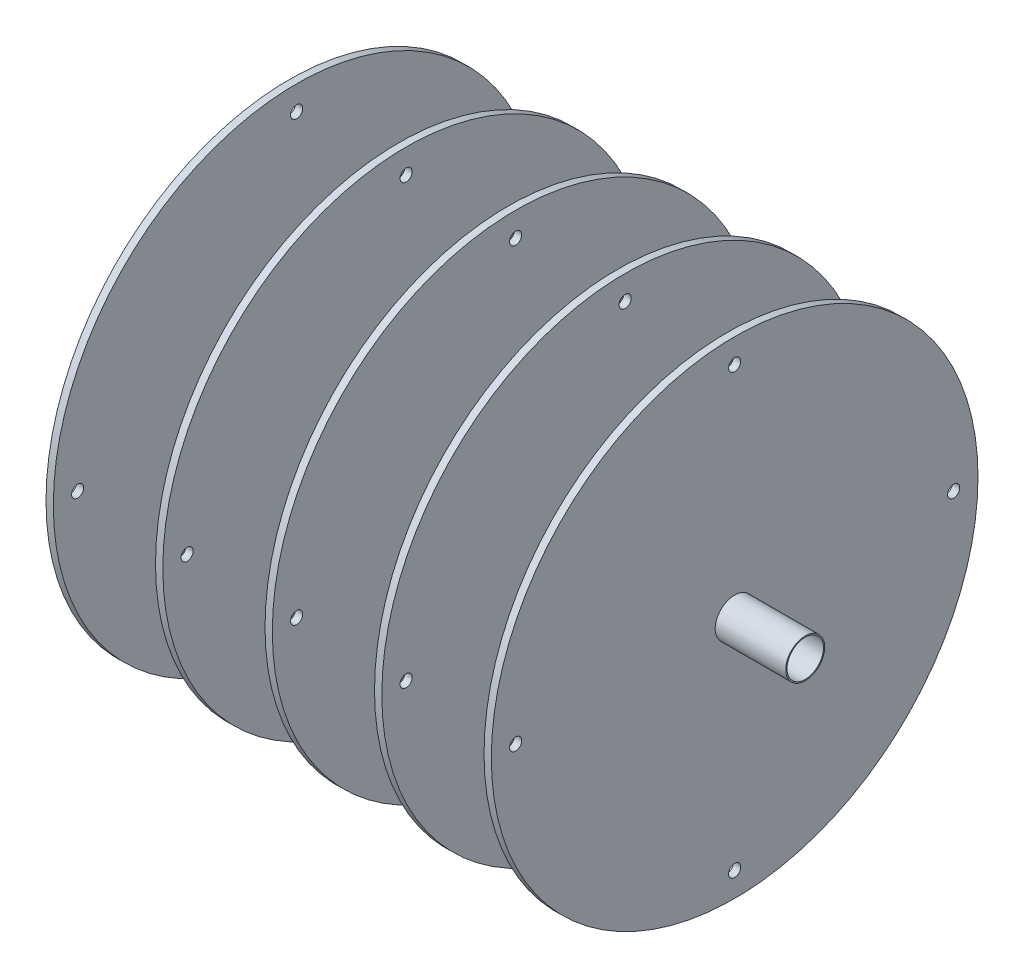
SolidWorks part; units mm, degrees
ref_plane "Front Plane" through (0, 0, 0) normal (0, 0, 1) x (1, 0, 0)
ref_plane "Top Plane" through (0, 0, 0) normal (0, 1, 0) x (1, 0, 0)
ref_plane "Right Plane" through (0, 0, 0) normal (1, 0, 0) x (0, 0, -1)
sketch "Sketch1" plane through (0, 0, 0) normal (1, 0, 0) x (0, 0, -1)
  circle A0 centre (0, 0) radius 8
  circle A1 centre (0, 0) radius 7.5
  dimension "D1" = 16
  dimension "D2" = 15
extrude "Boss-Extrude1" add sketch "Sketch1" along normal mid plane 243
ref_plane "Plane1" through (92.5, 0, 0) normal (1, 0, 0) x (0, 0, -1)
sketch "Sketch2" plane through (92.5, 0, 0) normal (1, 0, 0) x (0, 0, -1)
  circle A0 centre (0, 0) radius 100
  dimension "D1" = 200
extrude "Boss-Extrude2" add sketch "Sketch2" against normal blind 3
sketch "Sketch3" plane through (92.5, 0, 0) normal (1, 0, 0) x (0, 0, -1)
  circle A0 centre (0, 90) radius 2.5
  point P2 (0, 0)
  point P4 (0, 0)
  point P5 (0, 0)
  point P6 (0, 0)
  point P7 (0, 0)
  point P8 (0, 0)
  point P9 (0, 0)
  point P10 (0, 0)
  dimension "D1" = 5
  dimension "D2" = 90
extrude "Cut-Extrude1" cut sketch "Sketch3" against normal through all
pattern_circular "CirPattern1" count 4 over 360 about axis through (0, 0, 0) along (1, 0, 0) of "Cut-Extrude1"
pattern_linear "LPattern1" count 5 spacing 45 along (-1, 0, 0) of "CirPattern1", "Cut-Extrude1", "Boss-Extrude2"
